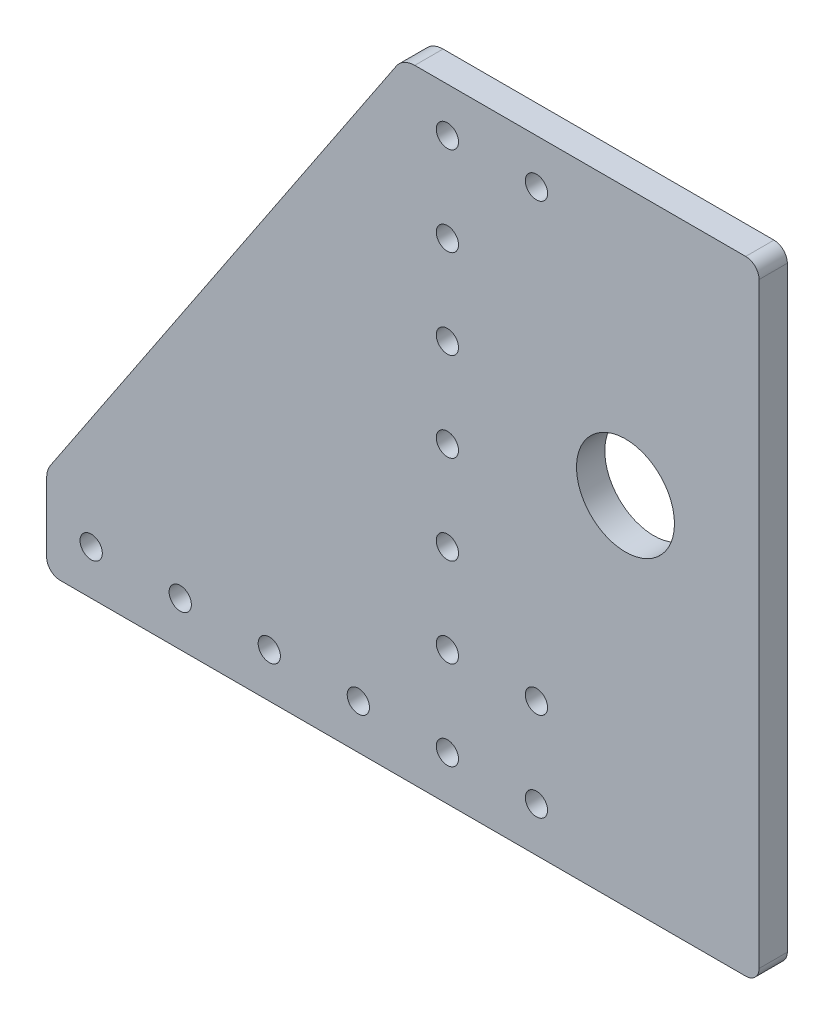
SolidWorks part; units mm, degrees
ref_plane "Front Plane" through (0, 0, 0) normal (0, 0, 1) x (1, 0, 0)
ref_plane "Top Plane" through (0, 0, 0) normal (0, 1, 0) x (1, 0, 0)
ref_plane "Right Plane" through (0, 0, 0) normal (1, 0, 0) x (0, 0, -1)
sketch "Sketch1" plane through (0, 0, 0) normal (0, 0, 1) x (1, 0, 0)
  line L0 (20, 61.8248) -> (-60, 61.8248)
  line L2 (-140, -78.1752) -> (20, -78.1752)
  line L3 (20, -78.1752) -> (20, 61.8248)
  line L4 (-140, -78.1752) -> (-140, -58.1752)
  line L5 (-140, -58.1752) -> (-60, 61.8248)
  line L6 (-60, 61.8248) -> (-60, -78.1752) construction
  line L7 (-140, -58.1752) -> (20, -58.1752) construction
  line L8 (-50, 61.8248) -> (-50, -58.1752) construction
  line L9 (-140, -68.1752) -> (20, -68.1752) construction
  circle A0 centre (-50, -48.1752) radius 2.5
  circle A1 centre (-50, -28.1752) radius 2.5
  circle A2 centre (-50, -8.1752) radius 2.5
  circle A3 centre (-50, 11.8248) radius 2.5
  circle A4 centre (-50, 31.8248) radius 2.5
  circle A5 centre (-50, 51.8248) radius 2.5
  circle A6 centre (-30, -48.1752) radius 2.5
  circle A7 centre (-30, 51.8248) radius 2.5
  circle A8 centre (-10, 1.8248) radius 11
  circle A9 centre (-30, -68.1752) radius 2.5
  circle A10 centre (-50, -68.1752) radius 2.5
  circle A11 centre (-70, -68.1752) radius 2.5
  circle A12 centre (-90, -68.1752) radius 2.5
  circle A13 centre (-110, -68.1752) radius 2.5
  circle A14 centre (-130, -68.1752) radius 2.5
  dimension "D5" = 10
  dimension "D6" = 5
  dimension "D9" = 10
  dimension "D10" = 22
  dimension "D13" = 5
  dimension "D14" = 6
  dimension "D1" = 140
  dimension "D2" = 80
  dimension "D3" = 20
  dimension "D4" = 10
  dimension "D11" = 40
  dimension "D12" = 80
  dimension "D7" = 6
  dimension "D8" = 2
extrude "Boss-Extrude1" add sketch "Sketch1" along normal blind 6.35
fillet "Fillet1" radius 5 2 edges at (-140, -58.1752, 3.175) (-60, 61.8248, 3.175)
fillet "Fillet2" radius 3 3 edges at (20, -78.1752, 3.175) (20, 61.8248, 3.175) (-140, -78.1752, 3.175)
